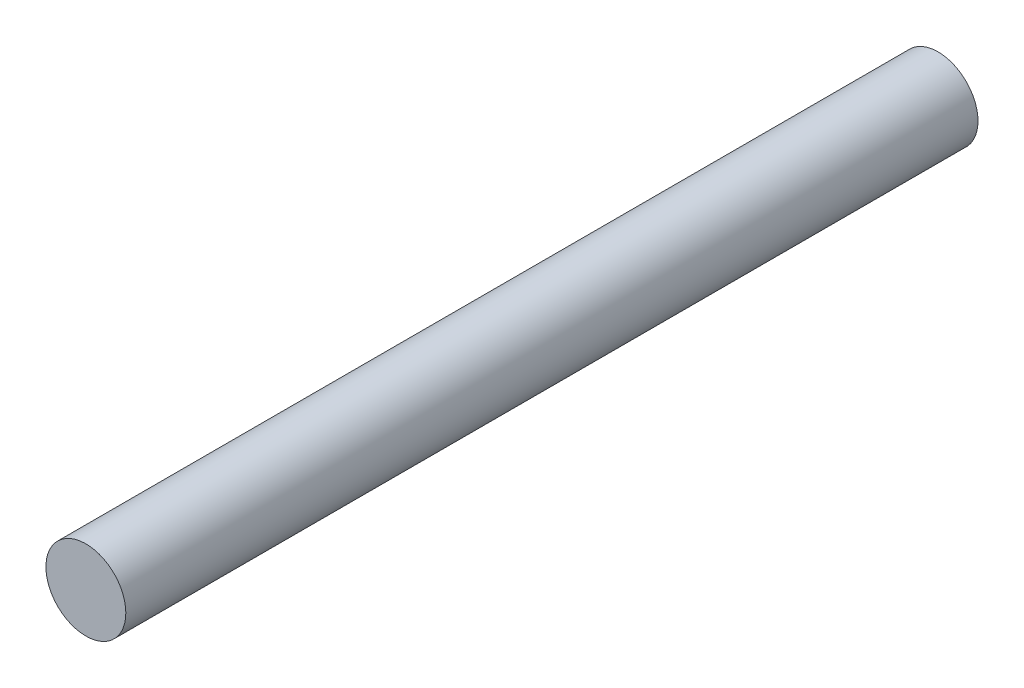
SolidWorks part; units mm, degrees
material "LW-PLA"
ref_plane "Front Plane" through (0, 0, 0) normal (0, 0, 1) x (1, 0, 0)
ref_plane "Top Plane" through (0, 0, 0) normal (0, 1, 0) x (1, 0, 0)
ref_plane "Right Plane" through (0, 0, 0) normal (1, 0, 0) x (0, 0, -1)
sketch "Sketch1" plane through (0, 0, 0) normal (0, 0, 1) x (1, 0, 0)
  circle A0 centre (0, 0) radius 0.75
  dimension "D1" = 1.5
extrude "Boss-Extrude1" add sketch "Sketch1" along normal blind 16
move or copy body "Body-Move/Copy1" bodies to move or copy 102 parameters "D1"=0, "D2"=0, "D3"=0
